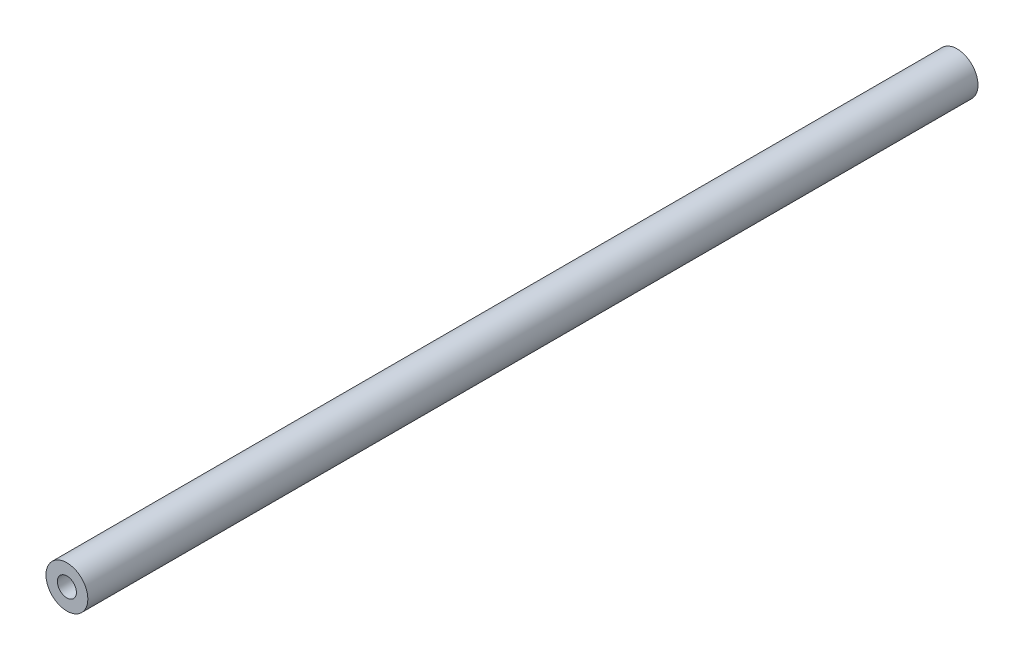
SolidWorks part; units mm, degrees
material "ABS"
ref_plane "Front Plane" through (0, 0, 0) normal (0, 0, 1) x (1, 0, 0)
ref_plane "Top Plane" through (0, 0, 0) normal (0, 1, 0) x (1, 0, 0)
ref_plane "Right Plane" through (0, 0, 0) normal (1, 0, 0) x (0, 0, -1)
sketch "Sketch1" plane through (0, 0, 0) normal (0, 0, 1) x (1, 0, 0)
  circle A0 centre (0, 0) radius 1.25
  circle A1 centre (0, 0) radius 2.75
  dimension "D1" = 2.5
  dimension "D2" = 5.5
extrude "Boss-Extrude1" add sketch "Sketch1" along normal blind 116.92
